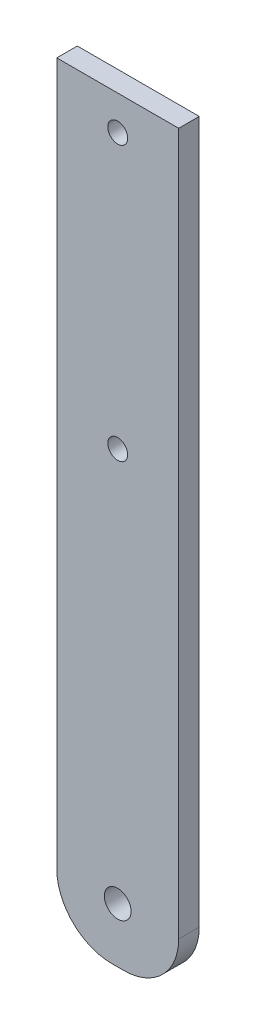
SolidWorks part; units mm, degrees
material "Thornel Mat VMA"
ref_plane "前视基准面" through (0, 0, 0) normal (0, 0, 1) x (1, 0, 0)
ref_plane "上视基准面" through (0, 0, 0) normal (0, 1, 0) x (1, 0, 0)
ref_plane "右视基准面" through (0, 0, 0) normal (1, 0, 0) x (0, 0, -1)
sketch "草图1" plane through (0, 0, 0) normal (0, 0, 1) x (1, 0, 0)
  line L0 (0, 0) -> (0, 102.5) construction
  line L1 (-8.9, -8) -> (8.9, -8)
  line L2 (-8.9, -8) -> (-8.9, 102.5)
  line L3 (-8.9, 102.5) -> (8.9, 102.5)
  line L4 (8.9, -8) -> (8.9, 102.5)
  line L5 (-8.9, -8) -> (8.9, 102.5) construction
  line L6 (-8.9, 102.5) -> (8.9, -8) construction
  circle A0 centre (0, 0) radius 1.95
  circle A1 centre (0, 57.5) radius 1.45
  circle A2 centre (0, 97.5) radius 1.45
  point P3 (0, 47.25)
  dimension "D1" = 3.9
  dimension "D3" = 17.8
  dimension "D5" = 2.9
  dimension "D6" = 40
  dimension "D7" = 5
  dimension "D4" = 97.5
  dimension "D2" = 8
extrude "凸台-拉伸1" add sketch "草图1" along normal blind 3
fillet "圆角1" radius 8 2 edges at (8.9, -8, 1.5) (-8.9, -8, 1.5)
